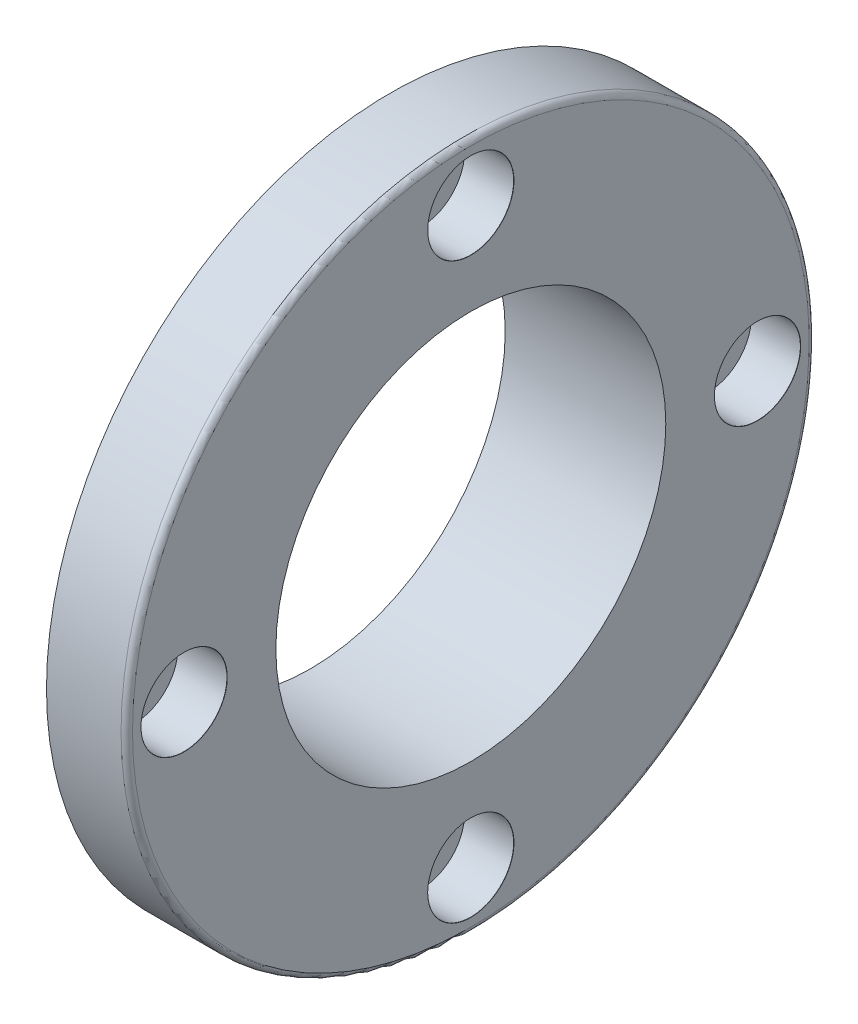
SolidWorks part; units mm, degrees
material "Thornel VCB-20 Carbon Cloth"
ref_plane "Plan de face" through (0, 0, 0) normal (0, 0, 1) x (1, 0, 0)
ref_plane "Plan de dessus" through (0, 0, 0) normal (0, 1, 0) x (1, 0, 0)
ref_plane "Plan de droite" through (0, 0, 0) normal (1, 0, 0) x (0, 0, -1)
sketch "Esquisse1" plane through (0, 0, 0) normal (0, 0, 1) x (1, 0, 0)
  line L0 (0, 0) -> (125.7857, 0) construction
  line L1 (81.5758, 40) -> (95.5758, 40)
  line L2 (95.5758, 40) -> (95.5758, 60)
  line L3 (95.5758, 60) -> (109.5758, 60)
  line L4 (109.5758, 60) -> (109.5758, 34)
  line L5 (109.5758, 34) -> (81.5758, 34)
  line L6 (81.5758, 34) -> (81.5758, 40)
  dimension "D1" = 80
  dimension "D2" = 28
  dimension "D3" = 14
  dimension "D4" = 20
  dimension "D5" = 68
  dimension "D6" = 26
revolve "Révolution1" add sketch "Esquisse1" angle 360 about L0
fillet "Congé1" radius 1 1 edges at (109.5758, 0, 60)
chamfer "Chanfrein1" distance 0.5 angle 45 1 edges at (81.5758, 0, 40)
sketch "Esquisse4" plane through (109.5758, 0, 0) normal (1, 0, 0) x (0, 0, -1)
  line L0 (0, 0) -> (0, 59) construction
  circle A0 centre (0, 0) radius 59 construction
hole_wizard "Chambrage pour vis à six pans creux M81" positions "Esquisse5" profile "Esquisse6" counterbore size "M8" standard "ISO" end condition through all
sketch "Esquisse5" plane through (109.5758, 0, 0) normal (1, 0, 0) x (0, 0, -1)
  line L0 (0, 0) -> (0, 59) construction
  point P0 (0, 50)
  dimension "Distance" = 50
sketch "Esquisse6" plane through (109.5758, 50, 0) normal (0, 1, 0) x (0, 0, -1)
  line L0 (0, 0) -> (0, 28)
  line L1 (0, 28) -> (4.5, 28)
  line L3 (4.5, 28) -> (4.5, 8.6)
  line L4 (7.5, 8.6) -> (4.5, 8.6)
  line L5 (7.5, 8.6) -> (7.5, 0.025)
  line L6 (7.5, 0.025) -> (7.525, 0)
  line L7 (7.525, 0) -> (0, 0)
  line L8 (-7.5, 0.025) -> (-7.525, 0) construction
  line L11 (0, -6.35) -> (0, 107.95) construction
  dimension "Diamètre du perçage jusqu'au prochain" = 9
  dimension "Profondeur du perçage jusqu'au prochain" = 28
  dimension "Diamètre du chambrage" = 15
  dimension "Profondeur du chambrage" = 8.6
  dimension "Diamètre du fraisage entrant" = 15.05
  dimension "Angle du fraisage entrant" = 90
pattern_circular "Répétition circulaire1" count 4 over 360 about axis through (0, 0, 0) along (1, 0, 0) of "Chambrage pour vis à six pans creux M81"
